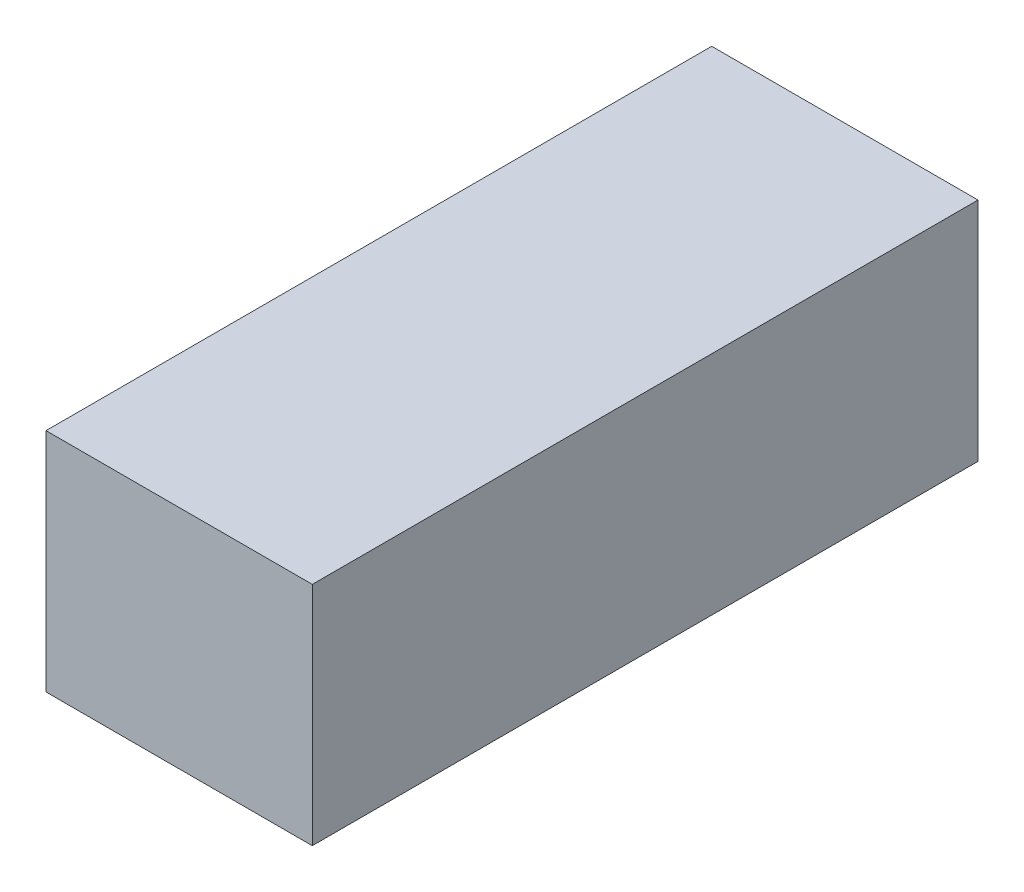
SolidWorks part; units mm, degrees
ref_plane "Front Plane" through (0, 0, 0) normal (0, 0, 1) x (1, 0, 0)
ref_plane "Top Plane" through (0, 0, 0) normal (0, 1, 0) x (1, 0, 0)
ref_plane "Right Plane" through (0, 0, 0) normal (1, 0, 0) x (0, 0, -1)
sketch "Sketch1" plane through (0, 0, 0) normal (0, 1, 0) x (1, 0, 0)
  line L1 (0, 0) -> (20, 0)
  line L2 (0, 0) -> (0, 50)
  line L3 (0, 50) -> (20, 50)
  line L4 (20, 0) -> (20, 50)
  dimension "D1" = 20
  dimension "D2" = 50
extrude "Boss-Extrude1" add sketch "Sketch1" along normal blind 17
